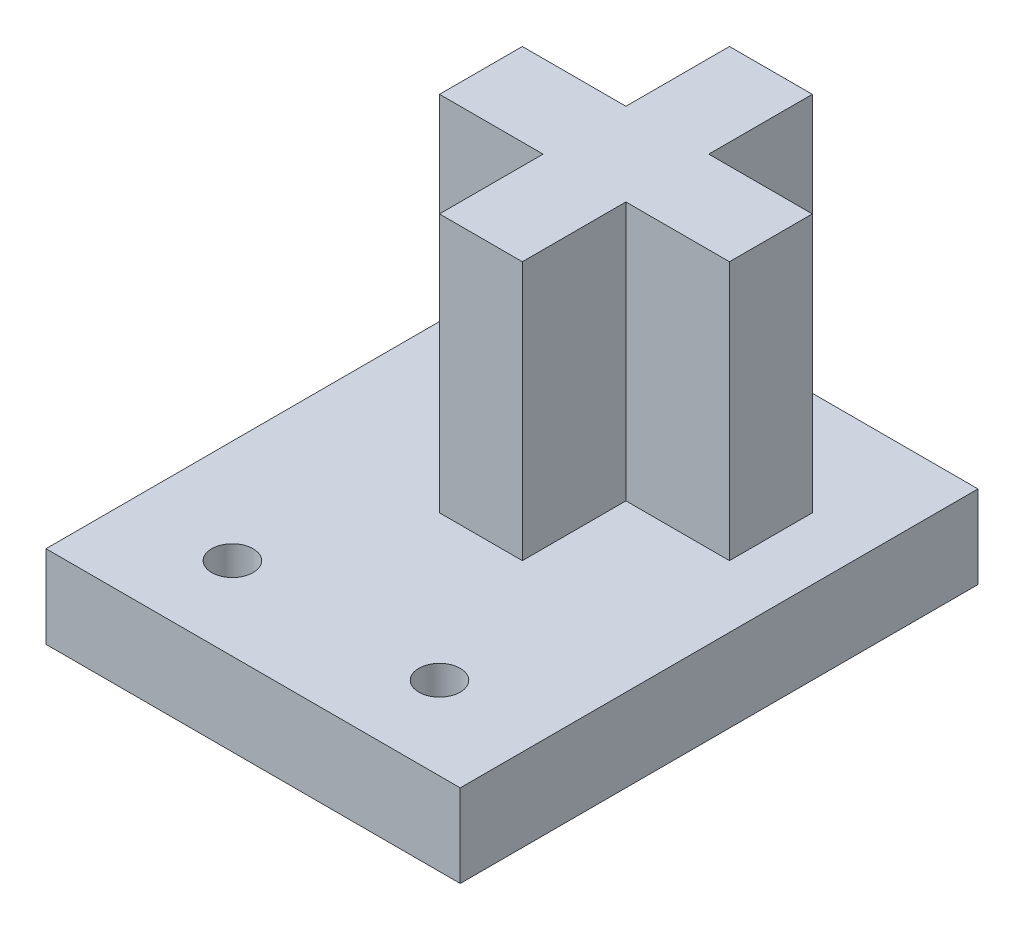
SolidWorks part; units mm, degrees
ref_plane "Front Plane" through (0, 0, 0) normal (0, 0, 1) x (1, 0, 0)
ref_plane "Top Plane" through (0, 0, 0) normal (0, 1, 0) x (1, 0, 0)
ref_plane "Right Plane" through (0, 0, 0) normal (1, 0, 0) x (0, 0, -1)
sketch "Sketch1" plane through (0, 0, 0) normal (0, 1, 0) x (1, 0, 0)
  line L0 (0, 0) -> (0, -24.0193) construction
  line L1 (-20, -25) -> (20, -25)
  line L2 (-20, -25) -> (-20, 25)
  line L3 (-20, 25) -> (20, 25)
  line L4 (20, -25) -> (20, 25)
  line L5 (-20, -25) -> (20, 25) construction
  line L6 (-20, 25) -> (20, -25) construction
  circle A0 centre (-10, -17) radius 2
  circle A1 centre (10, -17) radius 2
  point P0 (0, 0)
  dimension "D3" = 4
  dimension "D4" = 8
  dimension "D5" = 10
  dimension "D1" = 40
  dimension "D2" = 50
extrude "Boss-Extrude1" add sketch "Sketch1" along normal blind 8
sketch "Sketch2" plane through (0, 8, 0) normal (0, 1, 0) x (1, 0, 0)
  line L0 (-4, 25) -> (4, 25)
  line L1 (20, 25) -> (-20, 25) construction
  line L2 (4, 25) -> (4, 15)
  line L3 (4, 15) -> (14, 15)
  line L4 (14, 15) -> (14, 7)
  line L5 (14, 7) -> (4, 7)
  line L6 (4, 7) -> (4, -3)
  line L7 (4, -3) -> (-4, -3)
  line L8 (-4, -3) -> (-4, 7)
  line L9 (-4, 7) -> (-14, 7)
  line L10 (-14, 7) -> (-14, 15)
  line L11 (-14, 15) -> (-4, 15)
  line L12 (-4, 15) -> (-4, 25)
  point P5 (0, 25)
  dimension "D1" = 8
  dimension "D2" = 10
extrude "Boss-Extrude2" add sketch "Sketch2" along normal blind 25
